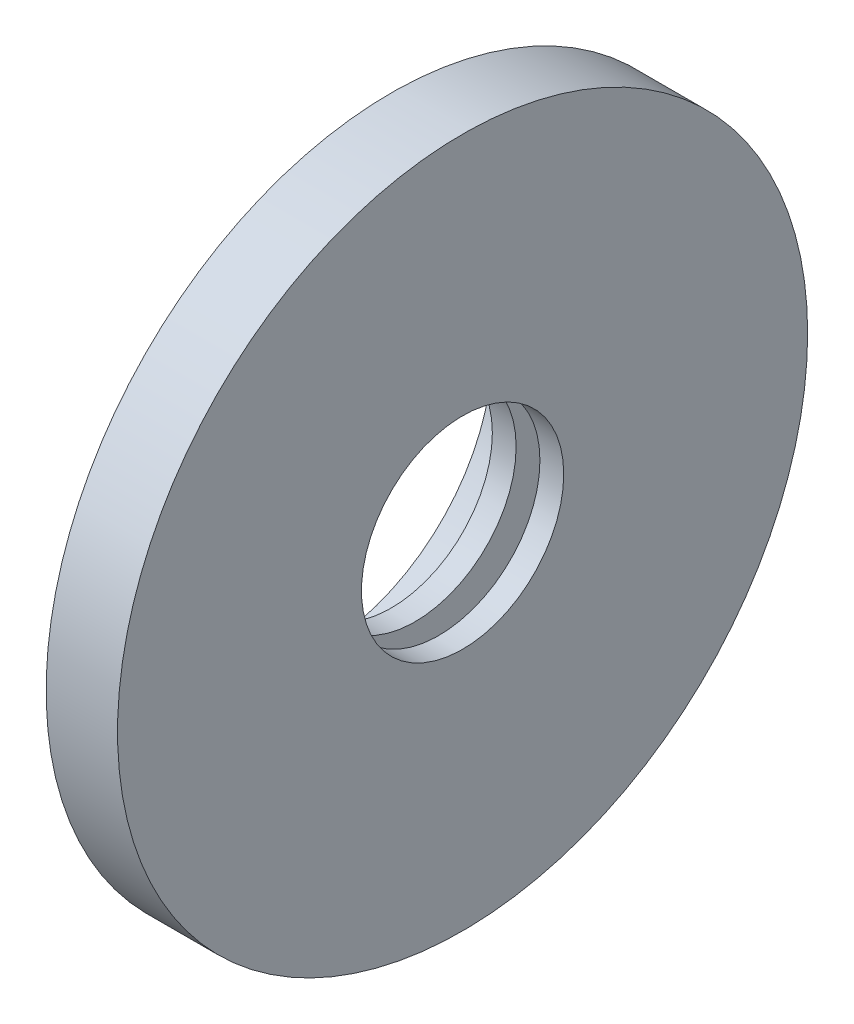
SolidWorks part; units mm, degrees
ref_plane "前视基准面" through (0, 0, 0) normal (0, 0, 1) x (1, 0, 0)
ref_plane "上视基准面" through (0, 0, 0) normal (0, 1, 0) x (1, 0, 0)
ref_plane "右视基准面" through (0, 0, 0) normal (1, 0, 0) x (0, 0, -1)
other "Configuration Table"
sketch "草图1" plane through (0, 0, 0) normal (0, 0, 1) x (1, 0, 0)
  line L0 (0, 0) -> (-24.0103, 0) construction
  line L1 (0, 0) -> (0, 14.5)
  line L2 (0, 14.5) -> (-6, 14.5)
  line L3 (-6, 14.5) -> (-6, 18.5)
  line L4 (-6, 18.5) -> (0, 18.5)
  line L5 (0, 18.5) -> (0, 29)
  line L6 (0, 29) -> (6, 29)
  line L7 (6, 29) -> (6, 0)
  line L8 (6, 0) -> (0, 0)
  dimension "D1" = 29
  dimension "D2" = 37
  dimension "D3" = 6
  dimension "D4" = 12
  dimension "D5" = 58
revolve "旋转1" add sketch "草图1" angle 360 about L0
sketch "草图2" plane through (0, 0, 0) normal (0, 0, 1) x (1, 0, 0)
  line L0 (0, 0) -> (-17.1558, 0) construction
  line L1 (0, 0) -> (0, 8.5)
  line L2 (0, 29) -> (0, -29) construction
  line L3 (0, 8.5) -> (2, 8.5)
  line L4 (2, 8.5) -> (2, 12.5)
  line L5 (2, 12.5) -> (4, 12.5)
  line L6 (4, 12.5) -> (4, 8.5)
  line L7 (4, 8.5) -> (6, 8.5)
  line L8 (6, -29) -> (6, 29) construction
  line L9 (6, 8.5) -> (6, 0)
  line L10 (6, 0) -> (0, 0)
  dimension "D1" = 17
  dimension "D2" = 25
  dimension "D3" = 2
  dimension "D4" = 2
revolve "切除-旋转1" cut sketch "草图2" angle 360 about L0
